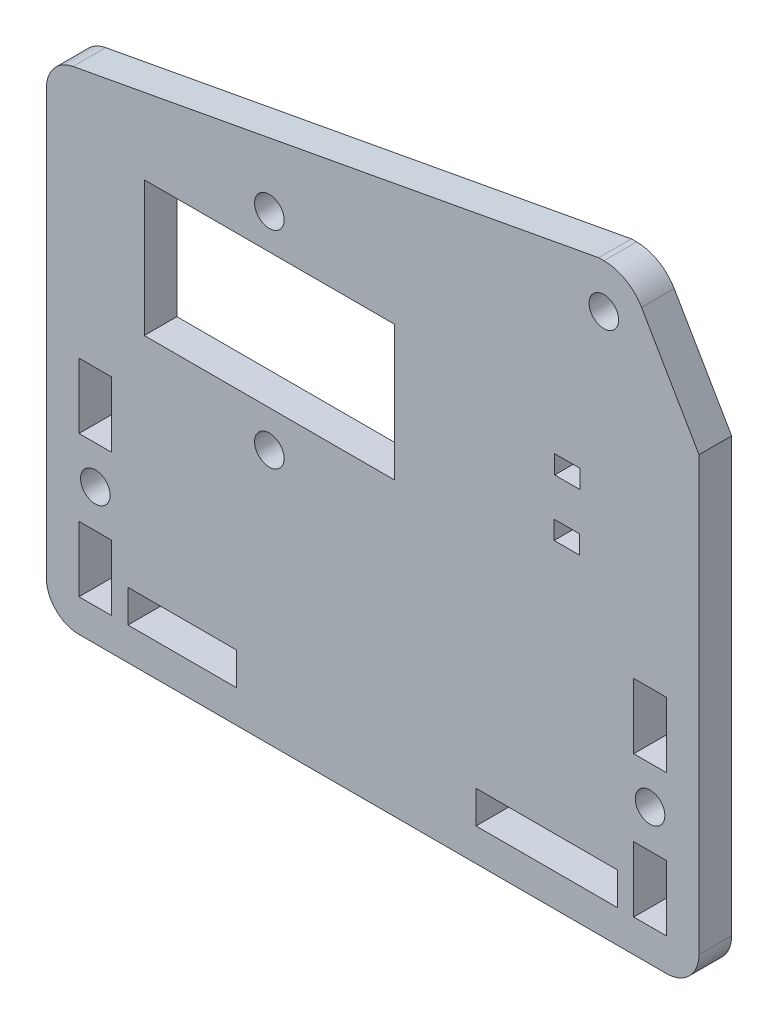
SolidWorks part; units mm, degrees
ref_plane "前视基准面" through (0, 0, 0) normal (0, 0, 1) x (1, 0, 0)
ref_plane "上视基准面" through (0, 0, 0) normal (0, 1, 0) x (1, 0, 0)
ref_plane "右视基准面" through (0, 0, 0) normal (1, 0, 0) x (0, 0, -1)
ref_plane "基准面1" through (0, 0, 3) normal (0, 0, 1) x (1, 0, 0)
sketch "草图1" plane through (0, 0, 3) normal (0, 0, 1) x (1, 0, 0)
  line L0 (46.679, 1.3587) -> (46.679, 3.0517)
  line L1 (46.679, 3.0517) -> (49.008, 3.0517)
  line L2 (49.008, 3.0517) -> (49.008, 1.3587)
  line L3 (49.008, 1.3587) -> (46.679, 1.3587)
  line L4 (46.731, 6.5977) -> (46.731, 8.2907)
  line L5 (46.731, 8.2907) -> (49.06, 8.2907)
  line L6 (49.06, 8.2907) -> (49.06, 6.5977)
  line L7 (49.06, 6.5977) -> (46.731, 6.5977)
  line L8 (39.5, -24.9643) -> (39.5, -21.9643)
  line L9 (39.5, -21.9643) -> (52.499, -21.9643)
  line L10 (52.499, -21.9643) -> (52.499, -24.9643)
  line L11 (52.499, -24.9643) -> (39.5, -24.9643)
  line L12 (7.5, -24.9643) -> (7.5, -21.9643)
  line L13 (7.5, -21.9643) -> (17.5, -21.9643)
  line L14 (17.5, -21.9643) -> (17.5, -24.9643)
  line L15 (17.5, -24.9643) -> (7.5, -24.9643)
  line L16 (54, -11.9653) -> (54, -5.9643)
  line L17 (54, -5.9643) -> (57, -5.9643)
  line L18 (57, -5.9643) -> (57, -11.9653)
  line L19 (57, -11.9653) -> (54, -11.9653)
  line L20 (54, -24.9643) -> (54, -18.9633)
  line L21 (54, -18.9633) -> (57, -18.9633)
  line L22 (57, -18.9633) -> (57, -24.9643)
  line L23 (57, -24.9643) -> (54, -24.9643)
  line L24 (3.001, -24.9643) -> (3.001, -18.9633)
  line L25 (3.001, -18.9633) -> (6.001, -18.9633)
  line L26 (6.001, -18.9633) -> (6.001, -24.9643)
  line L27 (6.001, -24.9643) -> (3.001, -24.9643)
  line L28 (3, -27.9644) -> (57, -27.9644)
  line L29 (60, -24.9644) -> (60, 14.8445)
  line L30 (60, 14.8445) -> (54.7215, 23.9306)
  line L31 (51.2628, 25.9213) -> (50.7826, 25.9213)
  line L32 (50.7826, 25.9213) -> (2.4546, 16.9856)
  line L33 (0, 14.0356) -> (0, -24.9644)
  line L34 (6.001, -11.9653) -> (3.001, -11.9653)
  line L35 (3.001, -11.9653) -> (3.001, -5.9643)
  line L36 (3.001, -5.9643) -> (6.001, -5.9643)
  line L37 (6.001, -5.9643) -> (6.001, -11.9653)
  line L38 (32, -1.1643) -> (9, -1.1643)
  line L39 (9, -1.1643) -> (9, 11.2347)
  line L40 (9, 11.2347) -> (32, 11.2347)
  line L41 (32, 11.2347) -> (32, -1.1643)
  circle A0 centre (51.251, 21.8697) radius 1.359
  circle A1 centre (20.499, 14.4657) radius 1.359
  circle A2 centre (20.499, -4.5353) radius 1.359
  circle A3 centre (4.5, -15.4643) radius 1.359
  circle A4 centre (55.5, -15.4643) radius 1.359
  arc A5 (57, -27.9644) -> (60, -24.9644) centre (57, -24.9644) ccw
  arc A6 (54.7215, 23.9306) -> (51.2628, 25.9213) centre (51.2628, 21.9213) ccw
  arc A7 (2.4546, 16.9856) -> (0, 14.0356) centre (3, 14.0356) ccw
  arc A8 (0, -24.9644) -> (3, -27.9644) centre (3, -24.9644) ccw
extrude "凸台-拉伸1" add sketch "草图1" against normal blind 3
